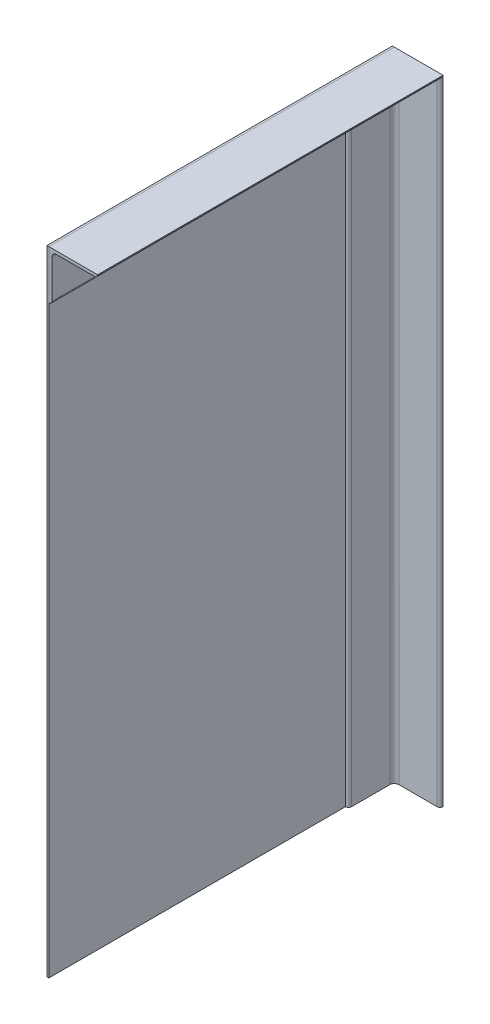
SolidWorks part; units mm, degrees
material "Fundición maleable"
ref_plane "Alzado" through (0, 0, 0) normal (0, 0, 1) x (1, 0, 0)
ref_plane "Planta" through (0, 0, 0) normal (0, 1, 0) x (1, 0, 0)
ref_plane "Vista lateral" through (0, 0, 0) normal (1, 0, 0) x (0, 0, -1)
sketch "Croquis1" plane through (0, 0, 0) normal (1, 0, 0) x (0, 0, -1)
  line L0 (0, 0) -> (-360, 0)
  line L1 (0, 0) -> (0, -660)
  dimension "D1" = 660
  dimension "D2" = 360
other "Hierro angular 2 X 2 X 0.125(1)"
ref_plane "Plano1" through (0, 0, 0) normal (0, 0, 1) x (0, -1, 0)
sketch "Sketch1" plane through (0, 0, 0) normal (0, 0, 1) x (0, -1, 0)
  line L0 (0, 0) -> (0, 50.8)
  line L1 (0, 50.8) -> (0.0051, 50.8)
  line L2 (3.175, 47.6301) -> (3.175, 7.9375)
  line L3 (7.9375, 3.175) -> (47.6301, 3.175)
  line L4 (50.8, 0.0051) -> (50.8, 0)
  line L5 (50.8, 0) -> (0, 0)
  arc A0 (50.8, 0.0051) -> (47.6301, 3.175) centre (47.6301, 0.0051) ccw
  arc A1 (0.0051, 50.8) -> (3.175, 47.6301) centre (0.0051, 47.6301) cw
  arc A2 (7.9375, 3.175) -> (3.175, 7.9375) centre (7.9375, 7.9375) cw
  point P10 (25.4, 0)
  point P14 (0, 25.4)
  point P15 (3.175, 25.4)
  point P16 (25.4, 3.175)
  point P17 (3.175, 50.8)
  point P18 (50.8, 3.175)
  point P19 (0, 0)
  dimension "D2" = 0.0051
  dimension "Radius_1" = 4.7625
  dimension "D1" = 3.175
  dimension "H_leg" = 50.8
sketch "Croquis2" plane through (0, 0, 0) normal (-1, 0, 0) x (0, 0, 1)
  line L1 (0, 0) -> (360, 0)
  line L2 (0, 0) -> (0, -660)
  line L3 (0, -660) -> (360, -660)
  line L4 (360, 0) -> (360, -660)
extrude "Saliente-Extruir1" add sketch "Croquis2" along normal blind 2 separate body
